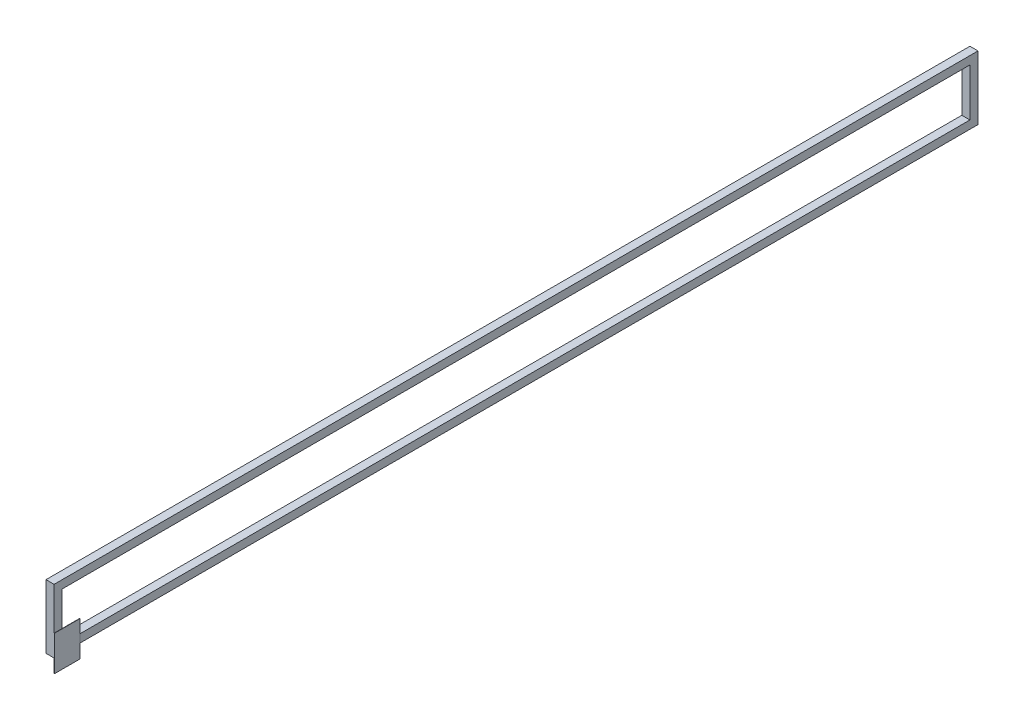
SolidWorks part; units mm, degrees
ref_plane "Alzado" through (0, 0, 0) normal (0, 0, 1) x (1, 0, 0)
ref_plane "Planta" through (0, 0, 0) normal (0, 1, 0) x (1, 0, 0)
ref_plane "Vista lateral" through (0, 0, 0) normal (1, 0, 0) x (0, 0, -1)
sketch "Croquis1" plane through (0, 0, 0) normal (0, 0, 1) x (1, 0, 0)
  line L1 (-25.4, -25.4) -> (25.4, -25.4)
  line L2 (-25.4, -25.4) -> (-25.4, 25.4)
  line L3 (-25.4, 25.4) -> (25.4, 25.4)
  line L4 (25.4, -25.4) -> (25.4, 25.4)
  line L5 (-25.4, -25.4) -> (25.4, 25.4) construction
  line L6 (-25.4, 25.4) -> (25.4, -25.4) construction
  point P0 (0, 0)
  dimension "D1" = 50.8
  dimension "D2" = 50.8
extrude "Saliente-Extruir1" add sketch "Croquis1" along normal blind 5800
sketch "Croquis4" plane through (25.4, 0, 0) normal (1, 0, 0) x (0, 0, -1)
  line L0 (-5800, 0) -> (-5640, 0) construction
  line L1 (-5800, -25.4) -> (-5800, 25.4) construction
  line L3 (-5800, -110) -> (-5640, -110)
  line L4 (-5800, -110) -> (-5800, 110)
  line L5 (-5800, 110) -> (-5640, 110)
  line L6 (-5640, -110) -> (-5640, 110)
  line L7 (-5800, -110) -> (-5640, 110) construction
  line L8 (-5800, 110) -> (-5640, -110) construction
  point P5 (-5720, 0)
  dimension "D1" = 160
  dimension "D2" = 220
extrude "Saliente-Extruir4" add sketch "Croquis4" along normal blind 1.9
sketch "Croquis5" plane through (25.4, 0, 0) normal (1, 0, 0) x (0, 0, -1)
  line L0 (0, 25.4) -> (0, 375.4)
  line L1 (0, 375.4) -> (-5800, 375.4)
  line L2 (-5800, 375.4) -> (-5800, 324.6)
  line L3 (-5800, 324.6) -> (-50.8, 324.6)
  line L4 (-50.8, 324.6) -> (-50.8, 25.4)
  line L5 (-5640, 25.4) -> (0, 25.4) construction
  line L6 (-50.8, 25.4) -> (0, 25.4)
  dimension "D1" = 50.8
  dimension "D2" = 50.8
  dimension "D3" = 350
  dimension "D4" = 5800
extrude "Saliente-Extruir5" add sketch "Croquis5" against normal up to surface (50.8 mm away) up to face at (-25.4, 0, 2900)
sketch "Croquis7" plane through (-25.4, 0, 0) normal (-1, 0, 0) x (0, 0, 1)
  line L0 (5800, 324.6) -> (5800, 25.4)
  line L1 (5800, 25.4) -> (5749.2, 25.4)
  line L2 (5800, 25.4) -> (50.8, 25.4) construction
  line L3 (5749.2, 25.4) -> (5749.2, 324.6)
  line L4 (50.8, 324.6) -> (5800, 324.6) construction
  line L5 (5749.2, 324.6) -> (5800, 324.6)
  dimension "D1" = 50.8
extrude "Saliente-Extruir7" add sketch "Croquis7" against normal up to surface (50.8 mm away) up to face at (25.4, 175, 2872.7)
